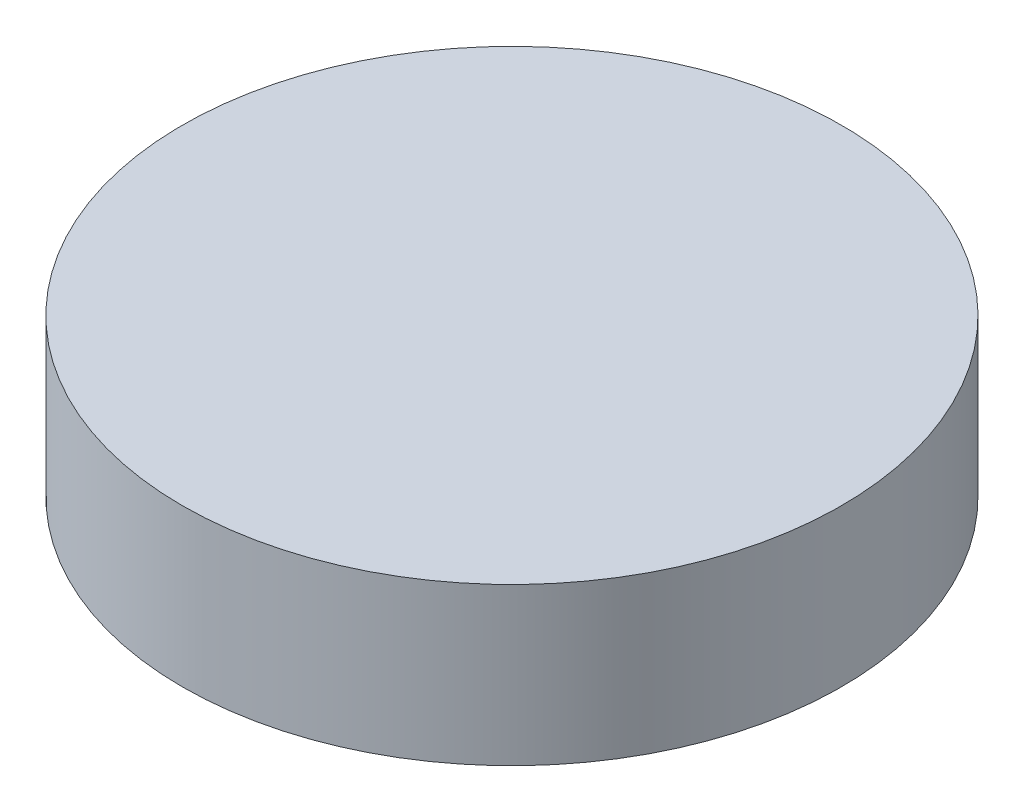
SolidWorks part; units mm, degrees
ref_plane "前基準面" through (0, 0, 0) normal (0, 0, 1) x (1, 0, 0)
ref_plane "上基準面" through (0, 0, 0) normal (0, 1, 0) x (1, 0, 0)
ref_plane "右基準面" through (0, 0, 0) normal (1, 0, 0) x (0, 0, -1)
sketch "草圖1" plane through (0, 0, 0) normal (0, 1, 0) x (1, 0, 0)
  circle A0 centre (0, 0) radius 10.5
extrude "填料-伸長1" add sketch "草圖1" along normal blind 5
